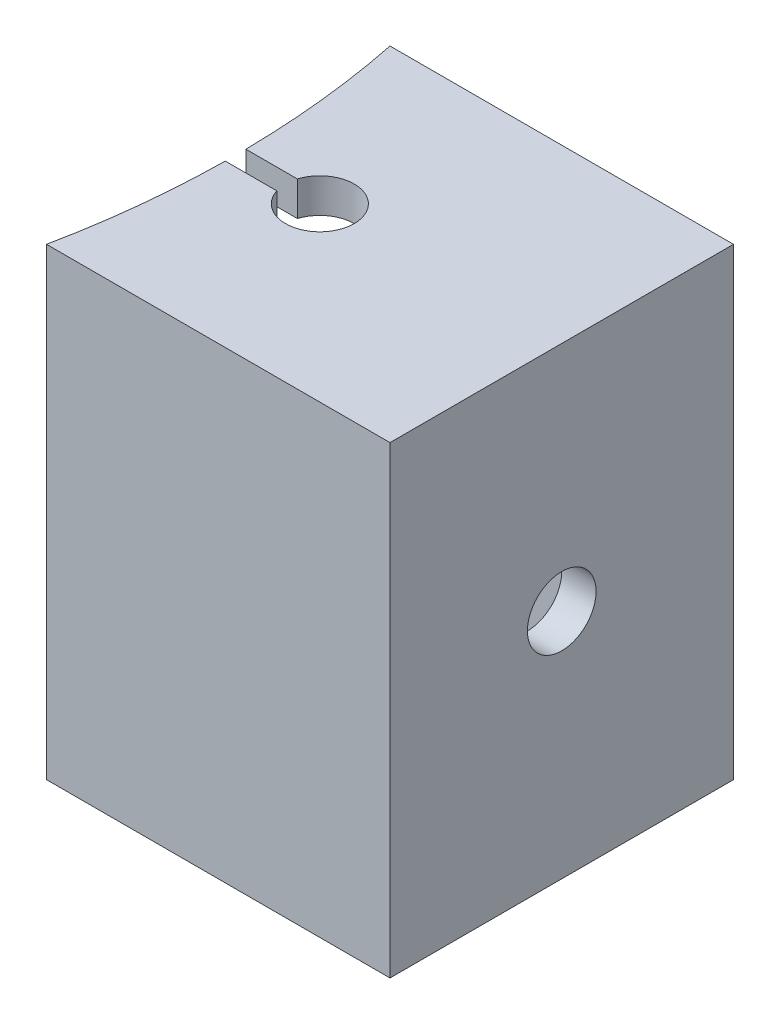
SolidWorks part; units mm, degrees
ref_plane "Front Plane" through (0, 0, 0) normal (0, 0, 1) x (1, 0, 0)
ref_plane "Top Plane" through (0, 0, 0) normal (0, 1, 0) x (1, 0, 0)
ref_plane "Right Plane" through (0, 0, 0) normal (1, 0, 0) x (0, 0, -1)
sketch "Sketch2" plane through (0, 0, 0) normal (0, 1, 0) x (1, 0, 0)
  line L0 (-18.9934, 10.6001) -> (-15.9934, 10.6001)
  line L1 (0, 0) -> (-20, 0)
  line L2 (0, 0) -> (0, 20)
  line L3 (0, 20) -> (-20, 20)
  line L4 (-18.9934, 9.4001) -> (-15.9934, 9.4001)
  arc A0 (-18.9934, 9.4001) -> (-20, 0) centre (-68.9898, 10) cw
  arc A1 (-20, 20) -> (-18.9934, 10.6001) centre (-68.9898, 10) cw
  arc A2 (-15.9934, 10.6001) -> (-15.9934, 9.4001) centre (-14.0855, 10.0001) cw
  point P11 (0, 0)
  point P12 (0, 0)
  dimension "D3" = 20
  dimension "D4" = 50
  dimension "D5" = 50
  dimension "D7" = 3
  dimension "D1" = 20
  dimension "D2" = 20
  dimension "D6" = 1.2
  dimension "D8" = 3
extrude "Boss-Extrude1" add sketch "Sketch2" along normal blind 27
shell "Shell3" thickness 2
sketch "Sketch3" plane through (0, 0, 0) normal (1, 0, 0) x (0, 0, -1)
  line L0 (0, 27) -> (20, 0)
  circle A0 centre (10, 13.5) radius 2
extrude "Cut-Extrude1" cut sketch "Sketch3" against normal blind 2 contours L0 A0 | L0 A0
